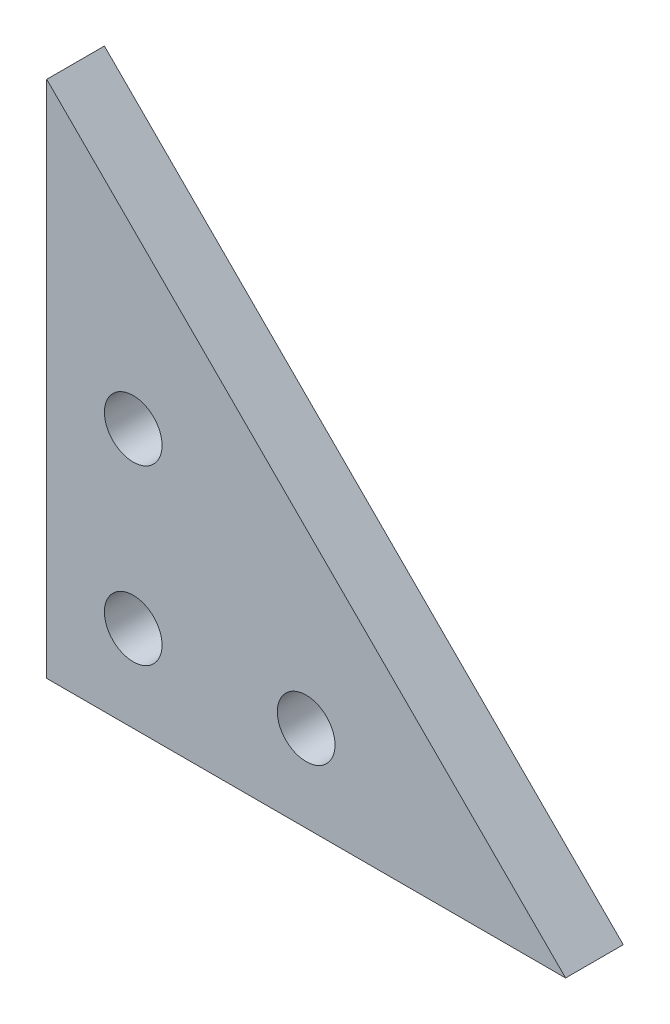
SolidWorks part; units mm, degrees
ref_plane "Alzado" through (0, 0, 0) normal (0, 0, 1) x (1, 0, 0)
ref_plane "Planta" through (0, 0, 0) normal (0, 1, 0) x (1, 0, 0)
ref_plane "Vista lateral" through (0, 0, 0) normal (1, 0, 0) x (0, 0, -1)
sketch "Model" plane through (0, 0, 0) normal (0, 0, 1) x (1, 0, 0)
  line L0 (-105.9434, 105.5565) -> (-105.9434, 78.5565)
  line L1 (-105.9434, 78.5565) -> (-78.9434, 78.5565)
  line L2 (-105.9434, 105.5565) -> (-78.9434, 78.5565)
  circle A0 centre (-101.4434, 92.0565) radius 1.5
  circle A1 centre (-101.4434, 83.0565) radius 1.5
  circle A2 centre (-92.4434, 83.0565) radius 1.5
extrude "Saliente-Extruir1" add sketch "Model" along normal blind 3
